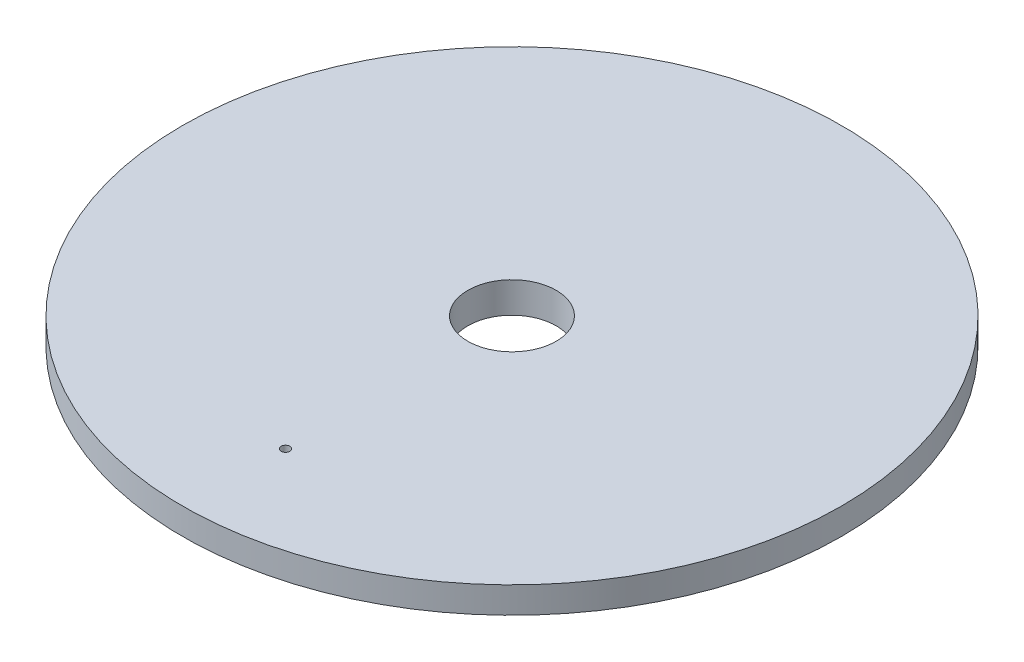
SolidWorks part; units mm, degrees
ref_plane "Front Plane" through (0, 0, 0) normal (0, 0, 1) x (1, 0, 0)
ref_plane "Top Plane" through (0, 0, 0) normal (0, 1, 0) x (1, 0, 0)
ref_plane "Right Plane" through (0, 0, 0) normal (1, 0, 0) x (0, 0, -1)
sketch "Szkic1" plane through (0, 0, 0) normal (0, 0, 1) x (1, 0, 0)
  line L0 (0, 0) -> (-75, 0)
  line L1 (-75, 0) -> (-75, -6)
  line L2 (-75, -6) -> (-59.4, -6)
  line L3 (-59.4, -6) -> (-59.4, -2.9)
  line L4 (-59.4, -2.9) -> (-54, -2.9)
  line L5 (-54, -2.9) -> (-54, -6)
  line L6 (-54, -6) -> (-50, -6)
  line L7 (-50, -6) -> (-50, -7.2)
  line L8 (-50, -7.2) -> (-46.9, -7.2)
  line L9 (-46.9, -7.2) -> (-46.9, -12.5)
  line L10 (-46.9, -12.5) -> (-50, -12.5)
  line L11 (-50, -12.5) -> (-50, -14.2516)
  line L12 (-50, -14.2516) -> (-45, -14.2516)
  line L13 (0, -7) -> (-43.7214, -7)
  line L14 (0, 0) -> (0, -7)
  line L15 (-43.7214, -7) -> (-45, -14.2516)
  line L16 (0, 0) -> (-10.055, 0)
  line L17 (-10.055, 0) -> (-10.055, -7)
  dimension "D1" = 75
  dimension "D2" = 6
  dimension "D3" = 59.4
  dimension "D4" = 3.1
  dimension "D5" = 50
  dimension "D6" = 54
  dimension "D7" = 1.2
  dimension "D8" = 46.9
  dimension "D9" = 3.1
  dimension "D10" = 5.3
  dimension "D11" = 45
  dimension "D12" = 7
  dimension "D13" = 100
  dimension "D14" = 10.055
revolve "Obrót1" add sketch "Szkic1" angle 360 about L14
sketch "Szkic2" plane through (0, -6, 0) normal (0, -1, 0) x (1, 0, 0)
  line L0 (0, 0) -> (0.4606, 53.998)
  line L1 (0.4606, 53.998) -> (0.4265, 49.9982)
  circle A0 centre (0, 0) radius 54 construction
  circle A1 centre (0, 0) radius 50 construction
  circle A2 centre (0.4435, 51.9848) radius 1
  dimension "D1" = 2
extrude "Wytnij-wyciągnięcie1" cut sketch "Szkic2" against normal blind 10 contours A2
